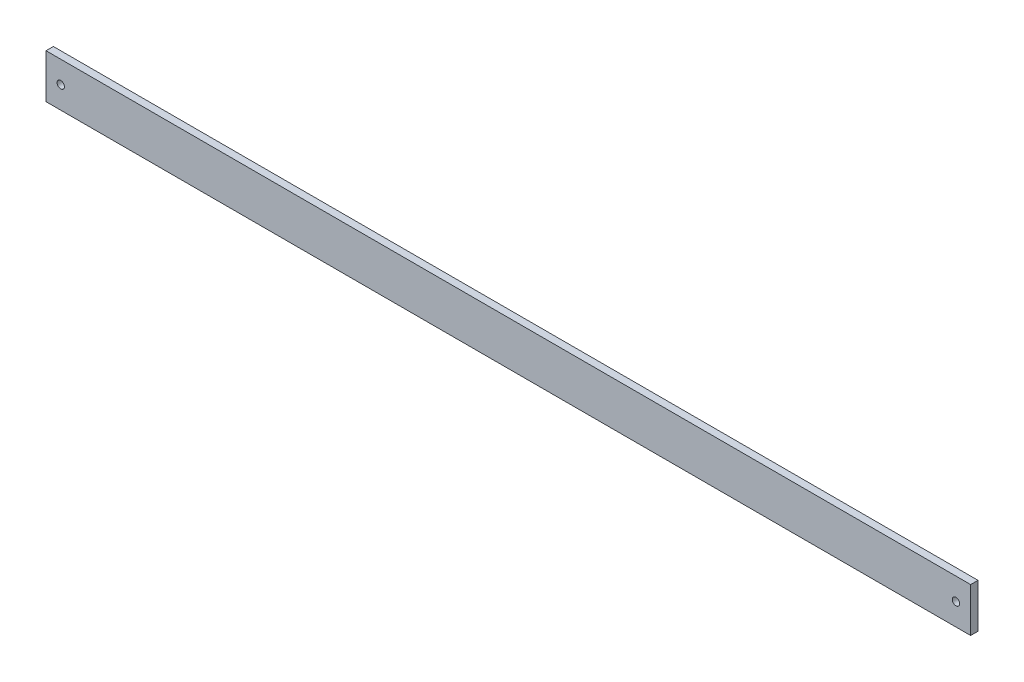
SolidWorks part; units mm, degrees
other "Markup1"
sketch "Sketch6" plane through (114.3, 38.1, 139.7) normal (0.0122, 0.8279, 0.5607) x (0.9984, -0.0412, 0.0392)
material "Balsa"
ref_plane "Front Plane" through (0, 0, 0) normal (0, 0, 1) x (1, 0, 0)
ref_plane "Top Plane" through (0, 0, 0) normal (0, 1, 0) x (1, 0, 0)
ref_plane "Right Plane" through (0, 0, 0) normal (1, 0, 0) x (0, 0, -1)
sketch "Sketch7" plane through (0, 0, 0) normal (0, 0, 1) x (1, 0, 0)
  line L1 (0, 0) -> (398.9578, 0)
  line L2 (0, 0) -> (0, 19.05)
  line L3 (0, 19.05) -> (398.9578, 19.05)
  line L4 (398.9578, 0) -> (398.9578, 19.05)
  circle A0 centre (6.35, 9.525) radius 1.5875
  circle A1 centre (392.6078, 9.525) radius 1.5875
  dimension "Hole Diameter" = 3.175
  dimension "Hole Diameter2" = 3.175
  dimension "Width" = 19.05
  dimension "Total Length" = 398.9578
  dimension "Hole Offset" = 6.35
  dimension "Length" = 386.2578
extrude "Boss-Extrude1" add sketch "Sketch7" along normal blind 3.175
equation "\"Width@Sketch7\" = \"w\""
equation "\"L1\"= 15in"
equation "\"L2\"= 12.5in"
equation "\"L3\"= 15.207in"
equation "\"L4\"= 15in"
equation "\"LL\"= 30in"
equation "\"w\"= 0.75in"
equation "\"t\"= 0.125in"
equation "\"holeD\" = 0.125in"
equation "\"holeOffset\" = 0.25in"
equation "\"Total Length@Sketch7\" = \"L\" + 2 * \"holeOffset\""
equation "\"L\"= \"L3\""
equation "\"Hole Diameter@Sketch7\"= \"holeD\""
equation "\"Hole Diameter2@Sketch7\"= \"Hole Diameter@Sketch7\""
equation "\"Hole Offset@Sketch7\"= \"holeOffset\""
equation "\"Length@Sketch7\"= \"L\""
equation "\"Thickness@Boss-Extrude1\"= \"t\""
